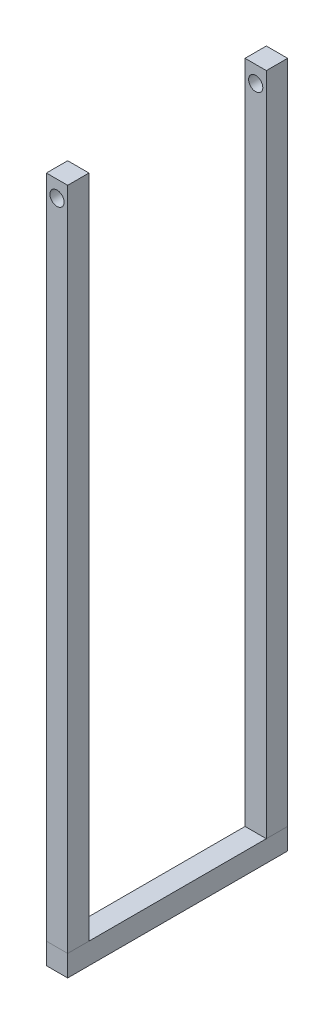
SolidWorks part; units mm, degrees
ref_plane "Front Plane" through (0, 0, 0) normal (0, 0, 1) x (1, 0, 0)
ref_plane "Top Plane" through (0, 0, 0) normal (0, 1, 0) x (1, 0, 0)
ref_plane "Right Plane" through (0, 0, 0) normal (1, 0, 0) x (0, 0, -1)
sketch "Sketch1" plane through (0, 0, 0) normal (0, 1, 0) x (1, 0, 0)
  line L1 (-6, -6) -> (6, -6)
  line L2 (-6, -6) -> (-6, 6)
  line L3 (-6, 6) -> (6, 6)
  line L4 (6, -6) -> (6, 6)
  line L5 (-6, -6) -> (6, 6) construction
  line L6 (-6, 6) -> (6, -6) construction
  point P0 (0, 0)
  dimension "D1" = 12
  dimension "D2" = 12
extrude "Boss-Extrude1" add sketch "Sketch1" along normal blind 375
sketch "Sketch2" plane through (0, 0, 6) normal (0, 0, 1) x (1, 0, 0)
  circle A0 centre (0, 365.6846) radius 4
sketch "Sketch3" plane through (0, 0, -6) normal (0, 0, -1) x (-1, 0, 0)
  line L1 (-6, 0) -> (6, 0)
  line L2 (-6, 0) -> (-6, -12)
  line L3 (-6, -12) -> (6, -12)
  line L4 (6, 0) -> (6, -12)
extrude "Boss-Extrude2" add sketch "Sketch3" against normal blind 124 separate body
sketch "Sketch4" plane through (0, 0, 0) normal (0, 1, 0) x (1, 0, 0)
  line L0 (-6, -118) -> (-6, 6) construction
  line L1 (6, -118) -> (-6, -118)
  line L2 (6, -118) -> (6, -106)
  line L3 (6, -106) -> (-6, -106)
  line L4 (-6, -118) -> (-6, -106)
extrude "Boss-Extrude3" add sketch "Sketch4" along normal blind 375 separate body
extrude "Cut-Extrude2" cut sketch "Sketch2" against normal through all and the other way through all
